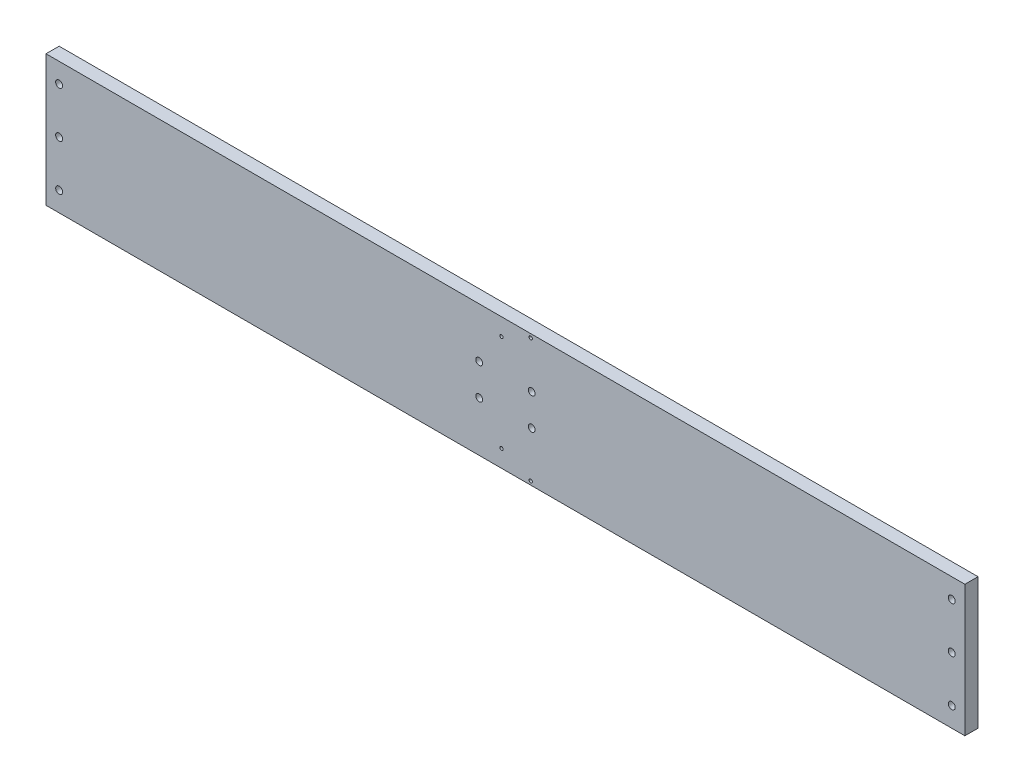
SolidWorks part; units mm, degrees
ref_plane "Piano frontale" through (0, 0, 0) normal (0, 0, 1) x (1, 0, 0)
ref_plane "Piano superiore" through (0, 0, 0) normal (0, 1, 0) x (1, 0, 0)
ref_plane "Piano destro" through (0, 0, 0) normal (1, 0, 0) x (0, 0, -1)
sketch "Schizzo1" plane through (0, 0, 0) normal (0, 0, 1) x (1, 0, 0)
  line L1 (0, 0) -> (700, 0)
  line L2 (0, 0) -> (0, 100)
  line L3 (0, 100) -> (700, 100)
  line L4 (700, 0) -> (700, 100)
  line L6 (350, 100) -> (350, 0) construction
  dimension "D1" = 100
  dimension "D2" = 700
extrude "Estrusione-Estrusione1" add sketch "Schizzo1" against normal blind 10
sketch "Schizzo2" plane through (0, 0, 0) normal (0, 0, 1) x (1, 0, 0)
  line L0 (350, 100) -> (350, 0) construction
  line L1 (700, 100) -> (0, 100) construction
  line L2 (0, 50) -> (700, 50) construction
  line L3 (0, 0) -> (700, 0) construction
  line L9 (0, 100) -> (0, 0) construction
  line L10 (700, 0) -> (700, 100) construction
  circle A0 centre (330, 62) radius 2.6
  circle A1 centre (370, 62) radius 2.6
  circle A2 centre (370, 38) radius 2.6
  circle A3 centre (330, 38) radius 2.6
  dimension "D3" = 5.2
  dimension "D1" = 12
  dimension "D2" = 20
extrude "Taglio-Estrusione1" cut sketch "Schizzo2" against normal through all
sketch "Sketch1" plane through (0, 0, 0) normal (0, 0, 1) x (1, 0, 0)
  point P0 (347.0471, 86.9)
  point P1 (369.2471, 97.2)
  point P3 (347.0471, 13.1)
  point P5 (369.2471, 2.8)
hole_wizard "M3 Tapped Hole1" positions "3DSketch1" profile "Sketch2" tap size "M3" standard "ISO"
sketch3d "3DSketch1"
  point P0 (369.2471, 97.2, 0)
  point P3 (347.0471, 86.9, 0)
  point P6 (347.0471, 13.1, 0)
  point P9 (369.2471, 2.8, 0)
sketch "Sketch2" plane through (369.2471, 97.2, 0) normal (1, 0, 0) x (0, -1, 0)
  line L0 (0, 0) -> (0, 12.2511)
  line L1 (0, 12.2511) -> (1.25, 11.5)
  line L2 (1.25, 11.5) -> (1.25, 0)
  line L5 (1.25, 0) -> (0, 0)
  line L10 (0, 12.2511) -> (-1.25, 11.5) construction
  line L11 (0, -6.35) -> (0, 107.95) construction
  dimension "Tap Drill Dia." = 2.5
  dimension "Tap Drill Depth" = 11.5
  dimension "Drill Angle" = 118
sketch "Sketch8" plane through (0, 0, -10) normal (0, 0, 1) x (1, 0, 0)
  line L0 (10, 100) -> (10, 0) construction
  line L1 (700, 100) -> (0, 100) construction
  line L2 (0, 0) -> (700, 0) construction
  line L3 (0, 100) -> (0, 0) construction
  line L4 (0, 50) -> (10, 50) construction
  line L5 (350, 100) -> (350, 0) construction
  point P10 (10, 85)
  point P11 (10, 50)
  point P12 (10, 15)
  point P15 (690, 15)
  point P16 (690, 50)
  point P17 (690, 85)
  dimension "D1" = 10
  dimension "D2" = 35
hole_wizard "CBORE for M5 SHCS1" positions "Sketch13" profile "Sketch12" counterbore size "M5" standard "ANSI Metric" end condition through all
sketch "Sketch13" plane through (0, 0, -10) normal (0, 0, 1) x (1, 0, 0)
  point P0 (10, 85)
  point P3 (10, 50)
  point P6 (10, 15)
  point P9 (690, 85)
  point P12 (690, 50)
  point P15 (690, 15)
sketch "Sketch12" plane through (10, 85, -10) normal (1, 0, 0) x (0, 1, 0)
  line L0 (0, 0) -> (0, 10)
  line L1 (0, 10) -> (2.65, 10)
  line L3 (2.65, 10) -> (2.65, 5)
  line L4 (2.65, 5) -> (5, 5)
  line L5 (5, 5) -> (5, 0)
  line L7 (5, 0) -> (0, 0)
  line L11 (0, -6.35) -> (0, 107.95) construction
  dimension "Thru Hole Dia." = 5.3
  dimension "Thru Hole Depth" = 10
  dimension "C'Bore Dia." = 10
  dimension "C'Bore Depth" = 5
